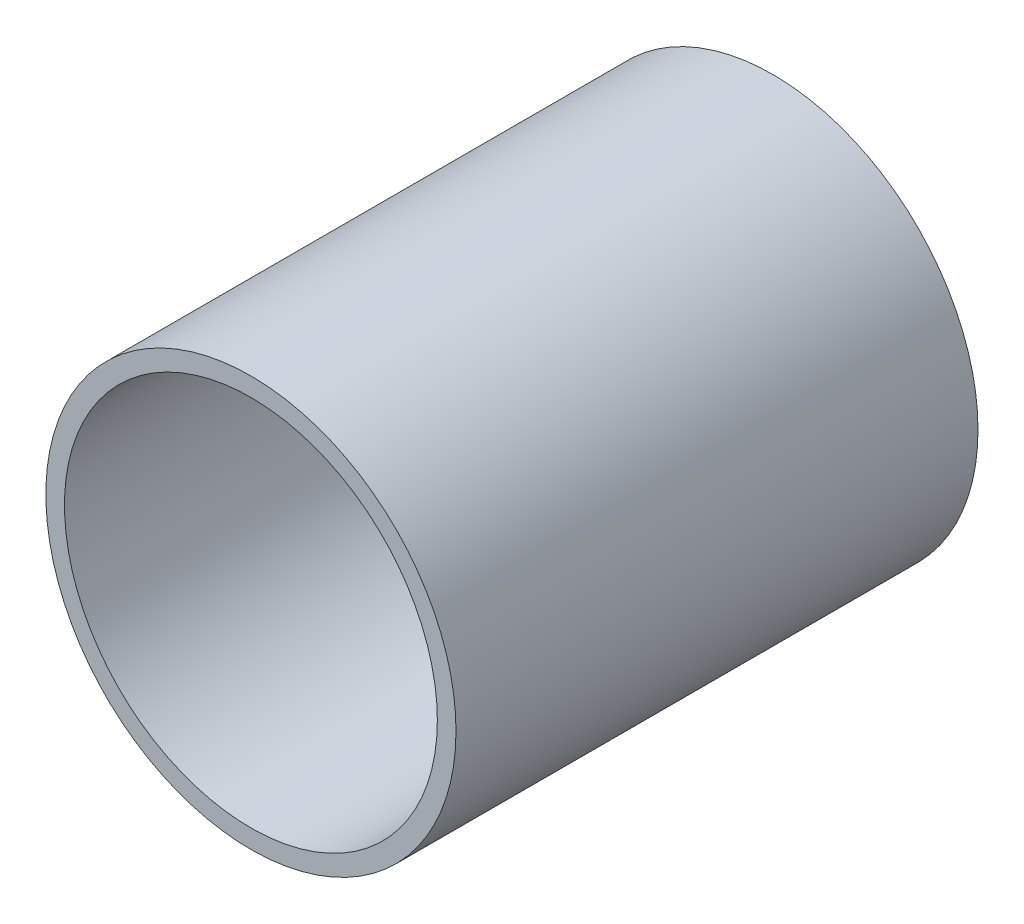
SolidWorks part; units mm, degrees
ref_plane "Front Plane" through (0, 0, 0) normal (0, 0, 1) x (1, 0, 0)
ref_plane "Top Plane" through (0, 0, 0) normal (0, 1, 0) x (1, 0, 0)
ref_plane "Right Plane" through (0, 0, 0) normal (1, 0, 0) x (0, 0, -1)
sketch "Sketch1" plane through (0, 0, 0) normal (0, 0, 1) x (1, 0, 0)
  circle A0 centre (0, 0) radius 69.85
  dimension "D1" = 139.7
extrude "Boss-Extrude1" add sketch "Sketch1" along normal blind 177.8
sketch "Sketch2" plane through (0, 0, 177.8) normal (0, 0, 1) x (1, 0, 0)
  circle A0 centre (0, 0) radius 25.4
  dimension "D1" = 50.8
extrude "Cut-Extrude1" cut sketch "Sketch2" against normal through all
sketch "Sketch3" plane through (0, 0, 177.8) normal (0, 0, 1) x (1, 0, 0)
  circle A0 centre (0, 0) radius 63.5
  dimension "D1" = 127
extrude "Cut-Extrude2" cut sketch "Sketch3" against normal blind 165.1
